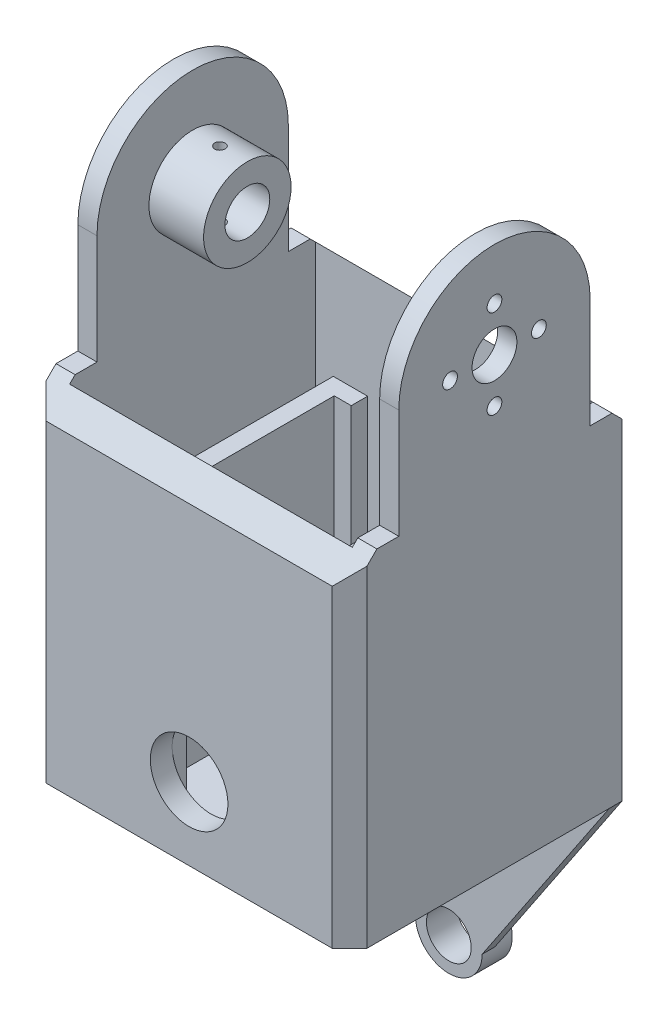
SolidWorks part; units mm, degrees
material "PLA"
ref_plane "Front Plane" through (0, 0, 0) normal (0, 0, 1) x (1, 0, 0)
ref_plane "Top Plane" through (0, 0, 0) normal (0, 1, 0) x (1, 0, 0)
ref_plane "Right Plane" through (0, 0, 0) normal (1, 0, 0) x (0, 0, -1)
sketch "Sketch1" plane through (0, 0, 0) normal (1, 0, 0) x (0, 0, -1)
  line L0 (-17.5, 0) -> (-17.5, -20)
  line L1 (17.5, 0) -> (17.5, -20)
  line L2 (17.5, -20) -> (22.5, -20)
  line L3 (-17.5, -20) -> (-22.5, -20)
  line L4 (22.5, -20) -> (22.5, -76)
  line L5 (-22.5, -20) -> (-22.5, -76)
  line L6 (22.5, -76) -> (-22.5, -76)
  arc A0 (17.5, 0) -> (-17.5, 0) centre (0, 0) ccw
  circle A1 centre (0, 0) radius 4.1
  dimension "D1" = 35
  dimension "D7" = 8.2
  dimension "D2" = 20
  dimension "D3" = 5
  dimension "D4" = 5
  dimension "D5" = 56
  dimension "D6" = 56
extrude "Boss-Extrude1" add sketch "Sketch1" against normal blind 3.5
sketch "Sketch2" plane through (0, 0, 0) normal (1, 0, 0) x (0, 0, -1)
  line L7 (-17.5, 0) -> (-17.5, -20)
  line L8 (-17.5, -20) -> (-22.5, -20)
  line L9 (-22.5, -20) -> (-22.5, -76)
  line L10 (-22.5, -76) -> (22.5, -76)
  line L11 (22.5, -76) -> (22.5, -20)
  line L12 (22.5, -20) -> (17.5, -20)
  line L13 (17.5, -20) -> (17.5, 0)
  line L16 (-22.5, -20) -> (-22.5, -76)
  line L17 (-22.5, -76) -> (22.5, -76)
  line L18 (22.5, -76) -> (22.5, -20)
  line L28 (-22.5, -20) -> (-26.5, -20)
  line L29 (-26.5, -20) -> (-26.5, -79.175)
  line L30 (22.5, -20) -> (26.5, -20)
  line L31 (26.5, -20) -> (26.5, -79.175)
  line L45 (-26.5, -79.175) -> (26.5, -79.175)
  arc A1 (17.5, 0) -> (-17.5, 0) centre (0, 0) ccw
  dimension "D2" = 4
  dimension "D3" = 4
  dimension "D1" = 0
extrude "Boss-Extrude2" add sketch "Sketch2" along normal blind 51.7 and the other way blind 3.5
chamfer "Chamfer2" distance 5 angle 45 2 edges at (24.1, -20, -26.5) (24.1, -20, 26.5)
sketch "Sketch4" plane through (0, -76, 0) normal (0, 1, 0) x (1, 0, 0)
  line L1 (0, 22.5) -> (51.7, 22.5)
  line L2 (0, 22.5) -> (0, -22.5)
  line L3 (0, -22.5) -> (51.7, -22.5)
  line L4 (51.7, 22.5) -> (51.7, -22.5)
extrude "Cut-Extrude1" cut sketch "Sketch4" against normal up to next
sketch "Sketch5" plane through (51.7, 0, 0) normal (1, 0, 0) x (0, 0, -1)
  line L9 (21.5, -20) -> (17.5, -20)
  line L10 (26.5, -25) -> (21.5, -20)
  line L11 (26.5, -79.175) -> (26.5, -25)
  line L12 (-26.5, -79.175) -> (26.5, -79.175)
  line L13 (-26.5, -25) -> (-26.5, -79.175)
  line L14 (-21.5, -20) -> (-26.5, -25)
  line L15 (-17.5, -20) -> (-21.5, -20)
  line L16 (-17.5, 0) -> (-17.5, -20)
  line L17 (17.5, -20) -> (17.5, 0)
  line L18 (21.5, -20) -> (17.5, -20)
  line L19 (26.5, -25) -> (21.5, -20)
  line L20 (26.5, -79.175) -> (26.5, -25)
  line L21 (-26.5, -79.175) -> (26.5, -79.175)
  line L22 (-26.5, -25) -> (-26.5, -79.175)
  line L23 (-21.5, -20) -> (-26.5, -25)
  line L24 (-17.5, -20) -> (-21.5, -20)
  line L25 (-17.5, 0) -> (-17.5, -20)
  line L26 (17.5, -20) -> (17.5, 0)
  arc A1 (17.5, 0) -> (-17.5, 0) centre (0, 0) ccw
  arc A2 (17.5, 0) -> (-17.5, 0) centre (0, 0) ccw
  circle A4 centre (0, 0) radius 4.1
  dimension "D2" = 8.2
  dimension "D1" = 0
extrude "Boss-Extrude3" add sketch "Sketch5" along normal blind 3.5
sketch "Sketch9" plane through (55.2, 0, 0) normal (1, 0, 0) x (0, 0, -1)
  circle A0 centre (0, 0) radius 8.125 construction
  circle A1 centre (0, 8.125) radius 1.35
  circle A2 centre (8.125, 0) radius 1.35
  circle A3 centre (0, -8.125) radius 1.35
  circle A4 centre (-8.125, 0) radius 1.35
  dimension "D1" = 16.25
  dimension "D2" = 2.7
  dimension "D3" = 2.7
  dimension "D4" = 2.7
  dimension "D5" = 2.7
extrude "Cut-Extrude3" cut sketch "Sketch9" against normal up to next
sketch "Sketch10" plane through (0, -79.175, 0) normal (0, -1, 0) x (1, 0, 0)
  line L2 (0, 22.5) -> (51.7, 22.5)
  line L9 (0, 22.5) -> (0, -22.5)
  line L10 (0, -22.5) -> (51.7, -22.5)
  line L11 (51.7, 22.5) -> (51.7, -22.5)
extrude "Boss-Extrude5" add sketch "Sketch10" along normal blind 3.175
sketch "Sketch26" plane through (0, 0, 26.5) normal (0, 0, 1) x (1, 0, 0)
  line L0 (25.85, -82.35) -> (25.85, -69.065) construction
  line L1 (55.2, -82.35) -> (-3.5, -82.35) construction
  circle A0 centre (25.85, -69.065) radius 7.1
  dimension "D1" = 14.2
extrude "Cut-Extrude6" cut sketch "Sketch26" against normal blind 4
sketch "Sketch27" plane through (0, -79.175, 0) normal (0, 1, 0) x (1, 0, 0)
  line L0 (13.4899, 12.1001) -> (13.4937, -19.3) construction
  line L1 (38.2062, -19.3) -> (38.2062, 12.1001) construction
  line L2 (25.85, -22.5) -> (25.85, 20.6118) construction
  line L3 (0, -22.5) -> (51.7, -22.5) construction
  line L4 (38.4062, -22.5) -> (38.4062, 12.1001)
  line L5 (13.2938, -22.5) -> (13.2938, 12.1001)
  line L6 (13.2938, 12.1001) -> (10.1188, 12.1001)
  line L7 (10.1188, 12.1001) -> (10.1188, -22.5)
  line L8 (10.1188, -22.5) -> (13.2938, -22.5)
  line L9 (38.4062, 12.1001) -> (41.5812, 12.1001)
  line L10 (41.5812, 12.1001) -> (41.5812, -22.5)
  line L11 (41.5812, -22.5) -> (38.4062, -22.5)
  dimension "D1" = 0.2
  dimension "D2" = 3.175
  dimension "D3" = 3.175
extrude "Boss-Extrude6" add sketch "Sketch27" along normal up to surface (45.22 mm away)
sketch "Sketch29" plane through (0, 0, -26.5) normal (0, 0, -1) x (-1, 0, 0)
  line L0 (-25.85, -82.35) -> (-25.85, -117.07) construction
  line L1 (3.5, -82.35) -> (-55.2, -82.35) construction
  line L2 (-55.2, -82.35) -> (-31.95, -117.07)
  line L3 (-19.75, -117.07) -> (3.5, -82.35)
  line L4 (-30.85, -103.5033) -> (-40.9973, -88.35)
  line L5 (3.5, -82.35) -> (-55.2, -82.35) construction
  line L6 (-20.85, -103.5033) -> (-10.7027, -88.35)
  line L7 (-40.9973, -88.35) -> (-40.9973, -82.35)
  line L8 (-10.7027, -88.35) -> (-10.7027, -82.35)
  line L9 (-30.85, -103.5033) -> (-20.85, -103.5033)
  circle A0 centre (-25.85, -117.07) radius 4.1
  circle A1 centre (-25.85, -117.07) radius 6.1
  dimension "D2" = 8.2
  dimension "D3" = 12.2
  dimension "D1" = 34.72
  dimension "D4" = 6
  dimension "D5" = 6
  dimension "D6" = 10
extrude "Boss-Extrude8" add sketch "Sketch29" against normal blind 5.5
chamfer "Chamfer3" distance 3.175 angle 45 6 edges at (-3.5, -53.675, -26.5) (55.2, -53.675, -26.5) (-3.5, -53.675, 26.5) (55.2, -53.675, 26.5) (43.575, -99.71, -26.5) (8.125, -99.71, -26.5)
sketch "Sketch30" plane through (0, 0, 0) normal (1, 0, 0) x (0, 0, -1)
  circle A0 centre (0, 0) radius 4.1
  circle A1 centre (0, 0) radius 8
  dimension "D1" = 8.2
  dimension "D2" = 16
extrude "Boss-Extrude9" add sketch "Sketch30" along normal blind 10
sketch "Sketch31" plane through (0, -20, 0) normal (0, 1, 0) x (1, 0, 0)
  line L0 (5, 8) -> (5, -8) construction
  line L1 (10, 8) -> (0, 8) construction
  line L2 (0, -8) -> (10, -8) construction
  circle A0 centre (5, 0) radius 0.95
  dimension "D1" = 1.9
extrude "Cut-Extrude7" cut sketch "Sketch31" along normal through all
sketch "Sketch32" plane through (0, -79.175, 0) normal (0, 1, 0) x (1, 0, 0)
  line L0 (13.7903, 12.4) -> (13.7903, 12.6) construction
  line L1 (15.4899, 12.4) -> (13.79, 12.4) construction
  line L2 (13.7903, 12.6) -> (16.4, 12.6) construction
  line L3 (16.6, 12.4) -> (16.6, 12.4787) construction
  line L4 (16.4, 12.6) -> (13.2938, 12.6)
  line L5 (13.2938, 12.1001) -> (13.2938, 12.6)
  line L6 (10.1188, 12.1001) -> (10.1188, 15.6001)
  line L7 (16.4, 12.6) -> (16.4, 15.6001)
  line L8 (16.4, 15.6001) -> (10.1188, 15.6001)
  line L9 (10.1188, 12.1001) -> (13.2938, 12.1001)
  line M12 (10.1188, 12.1001) -> (13.2938, 12.1001)
  dimension "D1" = 0.2
  dimension "D2" = 0.2
  dimension "D3" = 3.5
extrude "Boss-Extrude10" add sketch "Sketch32" along normal up to surface (45.22 mm away) contours L7 L8 L6 L5 L4 M12 up to face at (11.7063, -33.955, 5.1999)
sketch "Sketch33" plane through (0, -79.175, 0) normal (0, 1, 0) x (1, 0, 0)
  line L0 (13.1937, -19.6) -> (18.8801, -19.6) construction
  line L1 (13.2938, -22.5) -> (18.6801, -22.5)
  line L2 (13.2938, -22.5) -> (13.2938, -19.8)
  line L3 (13.2938, -19.8) -> (18.6801, -19.8)
  line L4 (18.6801, -22.5) -> (18.6801, -19.8)
  line L5 (13.7937, -19.6) -> (14.9937, -19.6) construction
  line L6 (18.85, -19.6) -> (19.084, -19.6) construction
  line L7 (18.8801, -19.6) -> (18.8801, -21.0143) construction
  dimension "D1" = 0.2
  dimension "D2" = 0.2
extrude "Boss-Extrude11" add sketch "Sketch33" along normal up to surface (45.22 mm away) up to face at (13.2709, -33.955, -1.9001)
ref_plane "Plane1" through (25.85, 0, 0) normal (-1, 0, 0) x (0, 0, 1)
mirror "Mirror1" about plane through (25.85, 0, 0) normal (-1, 0, 0) of "Boss-Extrude11", "Boss-Extrude10"
sketch "Sketch34" plane through (0, -33.955, 0) normal (0, 1, 0) x (1, 0, 0)
  line L0 (13.2938, -19.8) -> (13.2938, 12.6) construction
  line L1 (13.2938, 12.6) -> (16.4, 12.6) construction
  line L2 (16.4, 12.6) -> (16.4, 15.6001) construction
  line L3 (16.4, 15.6001) -> (10.1188, 15.6001) construction
  line L4 (10.1188, 15.6001) -> (10.1188, -22.5) construction
  line L5 (10.1188, -22.5) -> (18.6801, -22.5) construction
  line L6 (18.6801, -22.5) -> (18.6801, -19.8) construction
  line L7 (18.6801, -19.8) -> (13.2938, -19.8) construction
  line L8 (41.5812, -22.5) -> (41.5812, 15.6001) construction
  line L9 (41.5812, 15.6001) -> (35.3, 15.6001) construction
  line L10 (35.3, 15.6001) -> (35.3, 12.6) construction
  line L11 (35.3, 12.6) -> (38.4062, 12.6) construction
  line L12 (38.4062, 12.6) -> (38.4062, -19.8) construction
  line L13 (38.4062, -19.8) -> (33.0199, -19.8) construction
  line L14 (33.0199, -19.8) -> (33.0199, -22.5) construction
  line L15 (33.0199, -22.5) -> (41.5812, -22.5) construction
  line L16 (13.2938, -19.8) -> (13.2938, 12.6)
  line L17 (13.2938, 12.6) -> (16.4, 12.6)
  line L18 (16.4, 12.6) -> (16.4, 15.6001)
  line L19 (16.4, 15.6001) -> (10.1188, 15.6001)
  line L20 (10.1188, 15.6001) -> (10.1188, -22.5)
  line L21 (10.1188, -22.5) -> (18.6801, -22.5)
  line L22 (18.6801, -22.5) -> (18.6801, -19.8)
  line L23 (18.6801, -19.8) -> (13.2938, -19.8)
  line L24 (41.5812, -22.5) -> (41.5812, 15.6001)
  line L25 (41.5812, 15.6001) -> (35.3, 15.6001)
  line L26 (35.3, 15.6001) -> (35.3, 12.6)
  line L27 (35.3, 12.6) -> (38.4062, 12.6)
  line L28 (38.4062, 12.6) -> (38.4062, -19.8)
  line L29 (38.4062, -19.8) -> (33.0199, -19.8)
  line L30 (33.0199, -19.8) -> (33.0199, -22.5)
  line L31 (33.0199, -22.5) -> (41.5812, -22.5)
extrude "Boss-Extrude12" add sketch "Sketch34" along normal blind 0.2
